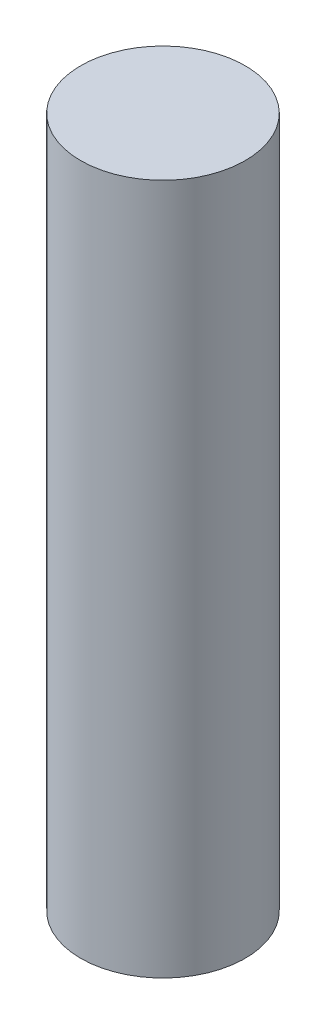
SolidWorks part; units mm, degrees
ref_plane "Front Plane" through (0, 0, 0) normal (0, 0, 1) x (1, 0, 0)
ref_plane "Top Plane" through (0, 0, 0) normal (0, 1, 0) x (1, 0, 0)
ref_plane "Right Plane" through (0, 0, 0) normal (1, 0, 0) x (0, 0, -1)
sketch "Sketch1" plane through (0, 0, 0) normal (0, 1, 0) x (1, 0, 0)
  circle A0 centre (0, 0) radius 4.7625
  dimension "D1" = 9.525
extrude "Boss-Extrude1" add sketch "Sketch1" along normal blind 40
